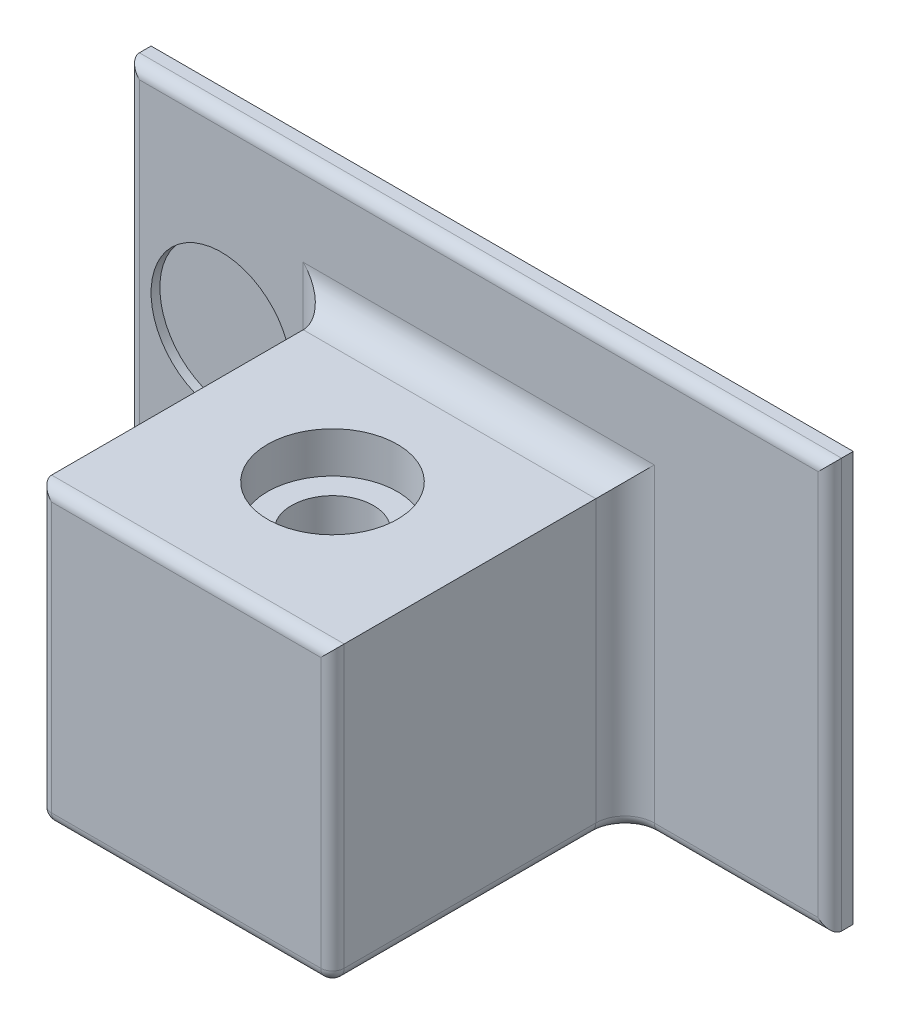
SolidWorks part; units mm, degrees
ref_plane "Front Plane" through (0, 0, 0) normal (1, 0, 0) x (0, 1, 0)
ref_plane "Top Plane" through (0, 0, 0) normal (0, 0, 1) x (0, 1, 0)
ref_plane "Right Plane" through (0, 0, 0) normal (0, 1, 0) x (-1, 0, 0)
sketch "Sketch1" plane through (0, 0, 0) normal (0, 0, 1) x (0, 1, 0)
  line L1 (-35, 60) -> (35, 60)
  line L2 (-35, 60) -> (-35, -60)
  line L3 (-35, -60) -> (35, -60)
  line L4 (35, 60) -> (35, -60)
  line L5 (-35, 60) -> (35, -60) construction
  line L6 (-35, -60) -> (35, 60) construction
  point P0 (0, 0)
  dimension "D1" = 70
  dimension "D2" = 120
extrude "Boss-Extrude1" add sketch "Sketch1" along normal blind 4
sketch "Sketch2" plane through (0, 0, 4) normal (0, 0, 1) x (1, 0, 0)
  line L0 (-60, -35) -> (60, -35) construction
  line L1 (-25, 15) -> (25, 15)
  line L2 (-25, 15) -> (-25, -35)
  line L3 (-25, -35) -> (25, -35)
  line L4 (25, 15) -> (25, -35)
  line L5 (-25, 15) -> (25, -35) construction
  line L6 (-25, -35) -> (25, 15) construction
  point P0 (0, -10)
  dimension "D1" = 50
  dimension "D2" = 50
extrude "Boss-Extrude2" add sketch "Sketch2" along normal blind 50
sketch "Sketch3" plane through (0, -35, 0) normal (0, -1, 0) x (1, 0, 0)
  line L0 (-25, 54) -> (25, 54) construction
  circle A0 centre (0, 29) radius 11.1
  dimension "D1" = 22.2
  dimension "D2" = 25
extrude "Cut-Extrude1" cut sketch "Sketch3" against normal blind 7
sketch "Sketch5" plane through (0, -28, 0) normal (0, -1, 0) x (1, 0, 0)
  circle A0 centre (0, 29) radius 7
  dimension "D1" = 14
extrude "Cut-Extrude3" cut sketch "Sketch5" against normal through all
sketch "Sketch6" plane through (0, 15, 0) normal (0, 1, 0) x (-1, 0, 0)
  circle A0 centre (0, 29) radius 11.1
  dimension "D1" = 22.2
extrude "Cut-Extrude4" cut sketch "Sketch6" against normal blind 7
sketch "Sketch7" plane through (0, 0, 4) normal (0, 0, 1) x (1, 0, 0)
  line L0 (25, -35) -> (60, -35) construction
  line L2 (-60, 35) -> (-60, -35) construction
  circle A0 centre (-44, 2.5) radius 12
  point P4 (-42.8788, -34)
  dimension "D1" = 24
  dimension "D3" = 16
  dimension "D2" = 37.5
extrude "Cut-Extrude5" cut sketch "Sketch7" against normal blind 1.5
fillet "Fillet1" radius 5 3 edges at (25, -10, 4) (0, 15, 4) (-25, -10, 4)
fillet "Fillet2" radius 2 13 edges at (25, -35, 31.5) (26.4645, -35, 5.4645) (-45, -35, 4) (-26.4645, -35, 5.4645) (60, 0, 4) (45, -35, 4) (0, 35, 4) (-60, 0, 4) (-25, -35, 31.5) (0, 15, 54) (25, -10, 54) (0, -35, 54) (-25, -10, 54)
